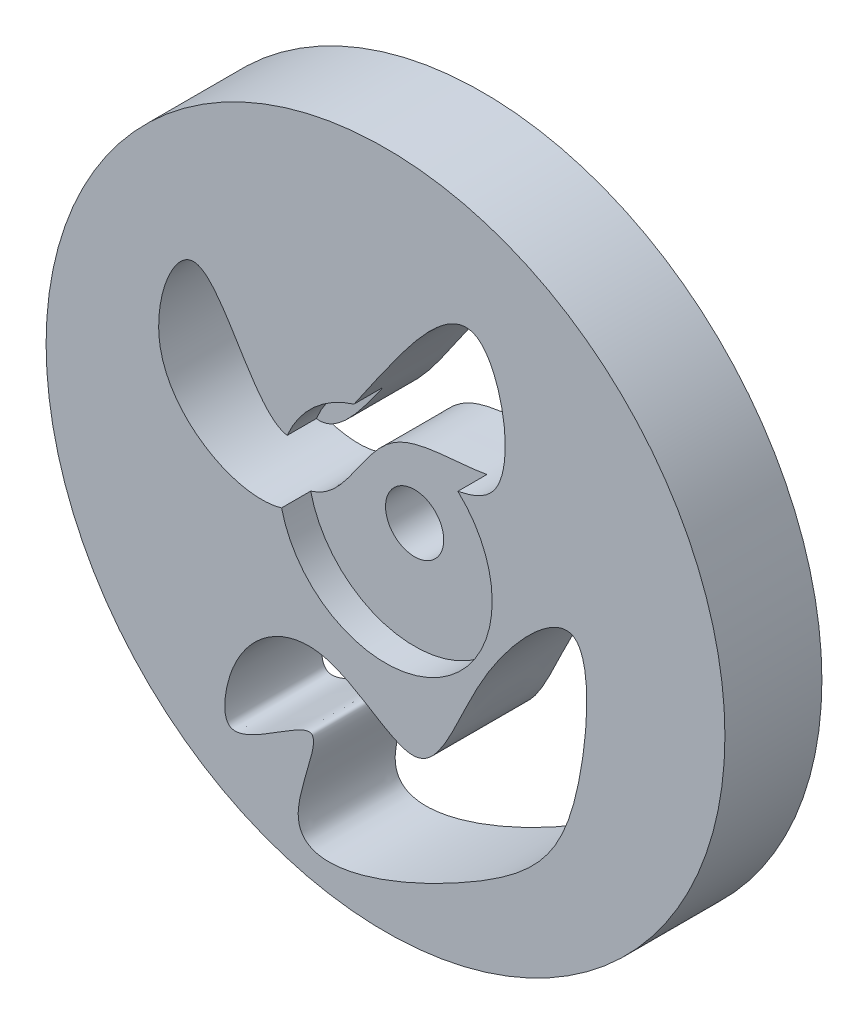
SolidWorks part; units mm, degrees
ref_plane "Front Plane" through (0, 0, 0) normal (0, 0, 1) x (1, 0, 0)
ref_plane "Top Plane" through (0, 0, 0) normal (0, 1, 0) x (1, 0, 0)
ref_plane "Right Plane" through (0, 0, 0) normal (1, 0, 0) x (0, 0, -1)
sketch "Sketch1" plane through (0, 0, 0) normal (0, 0, 1) x (1, 0, 0)
  circle A0 centre (19.925, -7) radius 35
  circle A1 centre (19.925, -7) radius 3
  spline S0 degree 3 poles (11.5941, -14.0335) (-7.162, -5.3659) (0.7924, 15.1407) (8.1072, -8.1643) (18.6841, 5.9192) (30.0043, 24.148) (34.8931, -1.9327) (16.2637, 3.1049) (11.5941, -14.0335) (-7.162, -5.3659) (0.7924, 15.1407) knots -0.38855 -0.25887 -0.147639 0 0.094983 0.231025 0.320787 0.491004 0.61145 0.74113 0.852361 1 1.094983 1.231025 1.320787 only from (-3.3038, -1.4114) to (-3.3038, -1.4114)
  spline S1 degree 3 poles (2.6876, -35.3294) (3.7963, -23.5713) (13.0159, -17.2751) (24.6269, -29.2263) (28.4672, -14.013) (41.7245, -0.2091) (40.2567, -23.3169) (33.0953, -32.361) (5.8064, -43.9952) (15.8305, -23.1541) (2.6876, -35.3294) (3.7963, -23.5713) (13.0159, -17.2751) knots -0.18067 -0.114958 -0.037403 0 0.099425 0.186607 0.296094 0.40158 0.513343 0.662291 0.81933 0.885042 0.962597 1 1.099425 1.186607 1.296094 only from (3.8435, -27.2464) to (3.8435, -27.2464)
  dimension "D1" = 70
extrude "Boss-Extrude1" add sketch "Sketch1" along normal blind 10
sketch "Sketch2" plane through (0, 0, 10) normal (0, 0, 1) x (1, 0, 0)
  circle A0 centre (19.925, -7) radius 11
  dimension "D1" = 22
extrude "Cut-Extrude1" cut sketch "Sketch2" against normal blind 3
